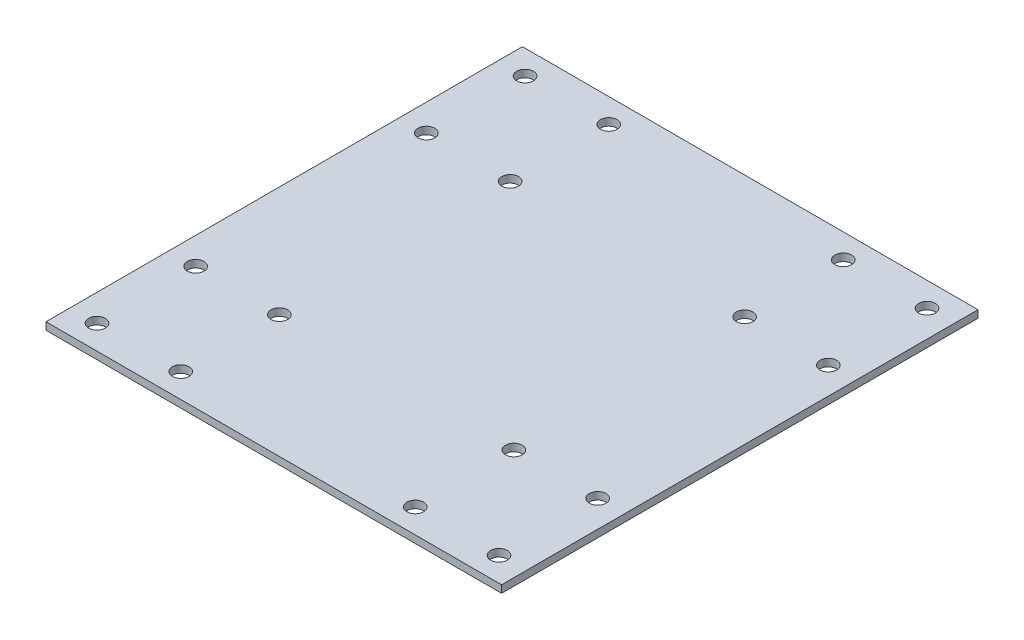
SolidWorks part; units mm, degrees
material "AISI 1020 Steel, Cold Rolled"
ref_plane "Front Plane" through (0, 0, 0) normal (0, 0, 1) x (1, 0, 0)
ref_plane "Top Plane" through (0, 0, 0) normal (0, 1, 0) x (1, 0, 0)
ref_plane "Right Plane" through (0, 0, 0) normal (1, 0, 0) x (0, 0, -1)
sketch "Sketch2" plane through (0, 0, 0) normal (0, 1, 0) x (1, 0, 0)
  line L1 (-194.31, -203.2) -> (194.31, -203.2)
  line L2 (-194.31, -203.2) -> (-194.31, 203.2)
  line L3 (-194.31, 203.2) -> (194.31, 203.2)
  line L4 (194.31, -203.2) -> (194.31, 203.2)
  line L5 (-194.31, -203.2) -> (194.31, 203.2) construction
  line L6 (-194.31, 203.2) -> (194.31, -203.2) construction
  point P0 (0, 0)
  dimension "D1" = 388.62
  dimension "D2" = 406.4
extrude "Boss-Extrude1" add sketch "Sketch2" along normal blind 6.35
sketch "Sketch3" plane through (0, 6.35, 0) normal (0, 1, 0) x (1, 0, 0)
  line L0 (-171.45, -182.5625) -> (171.45, -182.5625) construction
  line L1 (-194.31, -203.2) -> (194.31, -203.2) construction
  line L2 (-194.31, 203.2) -> (-194.31, -203.2) construction
  line L3 (194.31, -203.2) -> (194.31, 203.2) construction
  line L4 (-171.45, -182.5625) -> (-171.45, 182.5625) construction
  line L5 (-171.45, 182.5625) -> (171.45, 182.5625) construction
  line L6 (171.45, 182.5625) -> (171.45, -182.5625) construction
  line L7 (194.31, 203.2) -> (-194.31, 203.2) construction
  line L8 (100.0125, -182.5625) -> (100.0125, 182.5625) construction
  line L9 (-171.45, 98.425) -> (171.45, 98.425) construction
  line L10 (-171.45, -98.425) -> (-100.0125, -98.425) construction
  line L11 (-100.0125, -182.5625) -> (-100.0125, 182.5625) construction
  line L12 (171.45, -98.425) -> (100.0125, -98.425) construction
  circle A0 centre (-171.45, -182.5625) radius 7.1438
  circle A1 centre (-100.0125, 182.5625) radius 7.1437
  circle A2 centre (100.0125, -182.5625) radius 7.1438
  circle A3 centre (171.45, -182.5625) radius 7.1438
  circle A4 centre (-171.45, 182.5625) radius 7.1438
  circle A5 centre (-171.45, 98.425) radius 7.1438
  circle A6 centre (100.0125, 182.5625) radius 7.1438
  circle A7 centre (171.45, 182.5625) radius 7.1438
  circle A8 centre (-100.0125, -182.5625) radius 7.1437
  circle A9 centre (-171.45, -98.425) radius 7.1438
  circle A10 centre (-100.0125, -98.425) radius 7.1438
  circle A11 centre (-100.0125, 98.425) radius 7.1438
  circle A12 centre (100.0125, 98.425) radius 7.1438
  circle A13 centre (171.45, 98.425) radius 7.1438
  circle A14 centre (100.0125, -98.425) radius 7.1438
  circle A15 centre (171.45, -98.425) radius 7.1438
  dimension "D1" = 14.2875
  dimension "D8" = 71.4375
  dimension "D2" = 20.6375
  dimension "D3" = 22.86
  dimension "D4" = 84.1375
  dimension "D5" = 22.86
  dimension "D6" = 71.4375
  dimension "D7" = 20.6375
  dimension "D9" = 84.1375
  dimension "D10" = 84.1375
extrude "Cut-Extrude1" cut sketch "Sketch3" against normal through all
ref_plane "Plane1" through (0, 0, 182.5625) normal (0, 0, 1) x (1, 0, 0)
ref_plane "Plane2" through (0, 0, -182.5625) normal (0, 0, -1) x (-1, 0, 0)
sketch "Sketch6" plane through (0, 0, 182.5625) normal (0, 0, 1) x (1, 0, 0)
  line L0 (-171.45, 6.35) -> (-171.45, -57.3024) construction
  line L1 (171.45, 6.35) -> (171.45, -32.9995) construction
sketch "Sketch7" plane through (0, 0, -182.5625) normal (0, 0, -1) x (-1, 0, 0)
  line L0 (-171.45, 6.35) -> (-171.45, -34.7683) construction
  line L1 (171.45, 6.35) -> (171.45, -46.2715) construction
